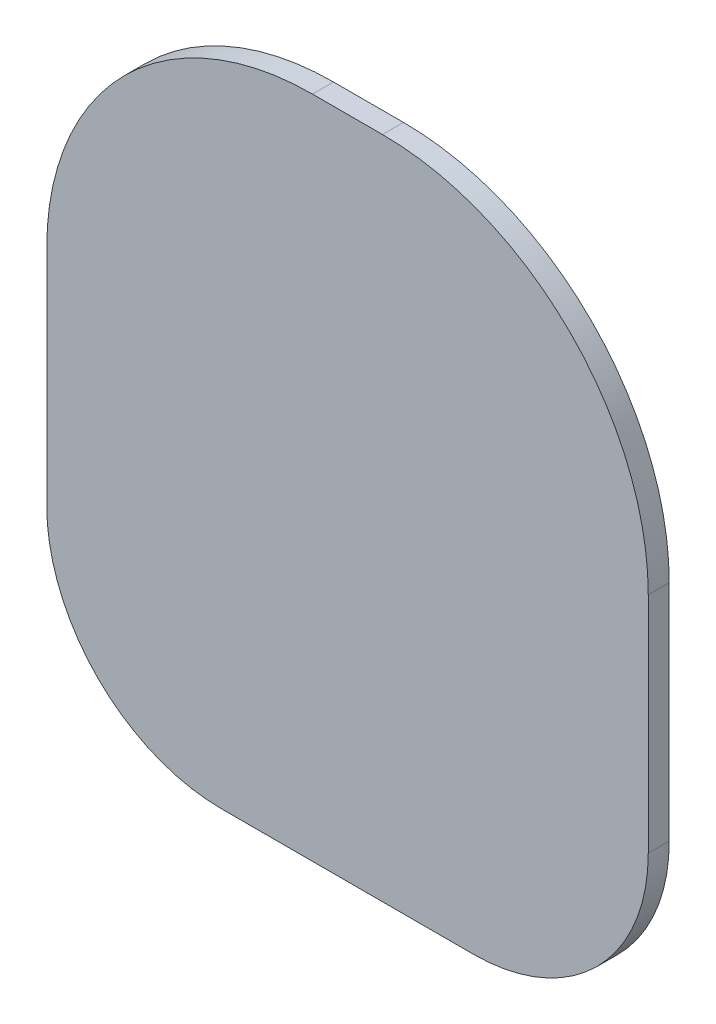
SolidWorks part; units mm, degrees
ref_plane "Front Plane" through (0, 0, 0) normal (0, 0, 1) x (1, 0, 0)
ref_plane "Top Plane" through (0, 0, 0) normal (0, 1, 0) x (1, 0, 0)
ref_plane "Right Plane" through (0, 0, 0) normal (1, 0, 0) x (0, 0, -1)
sketch "Sketch1" plane through (0, 0, 0) normal (0, 0, 1) x (1, 0, 0)
  line L0 (0, 8.5) -> (0, -86.5) construction
  line L1 (-43, 8.5) -> (43, 8.5) construction
  line L2 (-43, 8.5) -> (-43, -86.5) construction
  line L3 (-43, -86.5) -> (43, -86.5) construction
  line L4 (43, 8.5) -> (43, -86.5) construction
  line L5 (-5, 8.5) -> (5, 8.5)
  line L6 (-18, -86.5) -> (18, -86.5) construction
  line L7 (-43, -29.5) -> (43, -29.5) construction
  line L8 (-43, -29.5) -> (-43, -61.5)
  line L9 (-43, -61.5) -> (43, -61.5) construction
  line L10 (43, -29.5) -> (43, -61.5)
  line L11 (-0.5, -86.5) -> (0.5, -86.5) construction
  line L12 (-18, -86.5) -> (-0.5, -86.5)
  line L13 (0.5, -86.5) -> (18, -86.5)
  line L14 (-0.5, -86.5) -> (0.5, -86.5)
  line L15 (55, 0) -> (-55, 0) construction
  arc A0 (-43, -29.5) -> (-5, 8.5) centre (-5, -29.5) cw
  arc A1 (5, 8.5) -> (43, -29.5) centre (5, -29.5) cw
  arc A2 (-43, -61.5) -> (-18, -86.5) centre (-18, -61.5) ccw
  arc A3 (18, -86.5) -> (43, -61.5) centre (18, -61.5) ccw
  point P10 (0, 8.5)
  point P19 (0, -86.5)
  point P23 (0, -86.5)
  point P24 (0, 0)
  point P26 (0, 0)
  point P27 (10.793, 0)
  dimension "D3" = 25
  dimension "D4" = 38
  dimension "D1" = 95
  dimension "D2" = 86
  dimension "D5" = 1
  dimension "D6" = 8.5
extrude "Boss-Extrude1" add sketch "Sketch1" along normal blind 3
